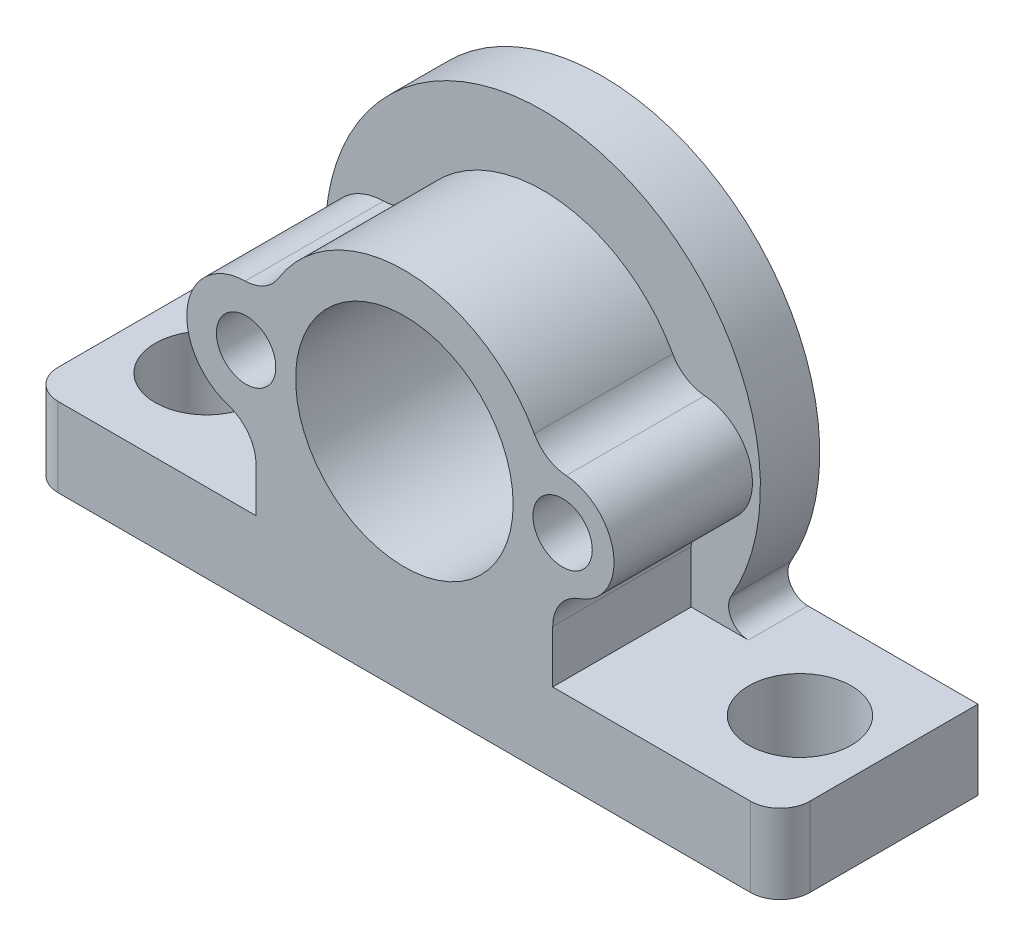
SolidWorks part; units mm, degrees
ref_plane "Front Plane" through (0, 0, 0) normal (0, 0, 1) x (1, 0, 0)
ref_plane "Top Plane" through (0, 0, 0) normal (0, 1, 0) x (1, 0, 0)
ref_plane "Right Plane" through (0, 0, 0) normal (1, 0, 0) x (0, 0, -1)
sketch "Sketch1" plane through (0, 0, 0) normal (0, 0, 1) x (1, 0, 0)
  line L0 (0, 7.5) -> (0, -11.0753) construction
  line L2 (7.5, -11) -> (-7.5, -11)
  line L3 (7.5, -11) -> (7.5, 0)
  line L4 (7.5, 0) -> (-7.5, 0)
  line L5 (-7.5, -11) -> (-7.5, 0)
  line L6 (7.5, -11) -> (-7.5, 0) construction
  line L7 (7.5, 0) -> (-7.5, -11) construction
  line L8 (-19, -7) -> (19, -7)
  line L9 (-19, -7) -> (-19, -11)
  line L10 (-19, -11) -> (19, -11)
  line L11 (19, -7) -> (19, -11)
  line L12 (-19, -7) -> (19, -11) construction
  line L13 (-19, -11) -> (19, -7) construction
  circle A0 centre (0, 0) radius 7.5
  circle A1 centre (0, 0) radius 5.5
  point P5 (0, -5.5)
  point P11 (0, -9)
  dimension "D2" = 2
  dimension "D3" = 11
  dimension "D1" = 11
  dimension "D4" = 4
  dimension "D5" = 38
extrude "Boss-Extrude1" add sketch "Sketch1" along normal blind 10 contours A1 L4 A0 | A1 L4 A0 | A0 L5 L8 | A0 L8 L3 | L8 L5 L2 L3 | L11 L8 L3 L10 | L9 L10 L5 L8 | L8 A0
sketch "Sketch2" plane through (0, -7, 0) normal (0, 1, 0) x (1, 0, 0)
  line L0 (19, -5) -> (-19, -5) construction
  line L3 (19, -10) -> (19, 0) construction
  line L6 (-19, -10) -> (-19, 0) construction
  line L7 (0, 0) -> (0, -10) construction
  line L8 (7.5, 0) -> (-7.5, 0) construction
  line L9 (-7.5, -10) -> (7.5, -10) construction
  circle A0 centre (-15, -5) radius 2.6
  circle A1 centre (15, -5) radius 2.6
  dimension "D1" = 5.2
  dimension "D2" = 30
extrude "Cut-Extrude1" cut sketch "Sketch2" against normal through all
sketch "Sketch3" plane through (0, 0, 0) normal (0, 0, -1) x (-1, 0, 0)
  circle A0 centre (0, 0) radius 5.5
  circle A1 centre (0, 0) radius 11
  dimension "D1" = 22
  dimension "D2" = 11
extrude "Boss-Extrude2" add sketch "Sketch3" against normal blind 3
sketch "Sketch4" plane through (0, 0, 0) normal (0, 0, -1) x (-1, 0, 0)
  line L0 (-11, 0) -> (11, 0) construction
  line L1 (0, 11) -> (0, -11) construction
  line L2 (19, -11) -> (-19, -11) construction
  circle A0 centre (0, 0) radius 11 construction
  circle A1 centre (8, 0) radius 1.5
  circle A2 centre (-8, 0) radius 1.5
  dimension "D1" = 3
  dimension "D2" = 16
extrude "Cut-Extrude2" cut sketch "Sketch4" against normal through all
sketch "Sketch5" plane through (0, 0, 10) normal (0, 0, 1) x (1, 0, 0)
  circle A0 centre (8, 0) radius 2.6
  circle A1 centre (-8, 0) radius 3
  circle A2 centre (-8, 0) radius 1.5
  circle A3 centre (8, 0) radius 1.5
  circle A4 centre (0, 0) radius 5.5
  arc M2 (7.375, 1.3636) -> (-7.375, 1.3636) centre (0, 0) ccw
  line M4 (-7.5, -1.4142) -> (-7.5, -7)
  line M10 (7.5, -7) -> (7.5, -1.4142)
  dimension "D1" = 6
  dimension "D2" = 5.2
extrude "Boss-Extrude3" add sketch "Sketch5" against normal through all contours A2 A1 M2 M4 | A3 A0 M10 M2
fillet "Fillet1" radius 2 4 edges at (-7.5, -2.958, 6.5) (7.5, -2.5515, 6.5) (7.0931, 2.4367, 6.5) (-6.9531, 2.8114, 6.5)
fillet "Fillet2" radius 1.5 2 edges at (19, -9, 10) (-19, -9, 10)
fillet "Fillet3" radius 1 2 edges at (8.4853, -7, 1.5) (-8.4853, -7, 1.5)
